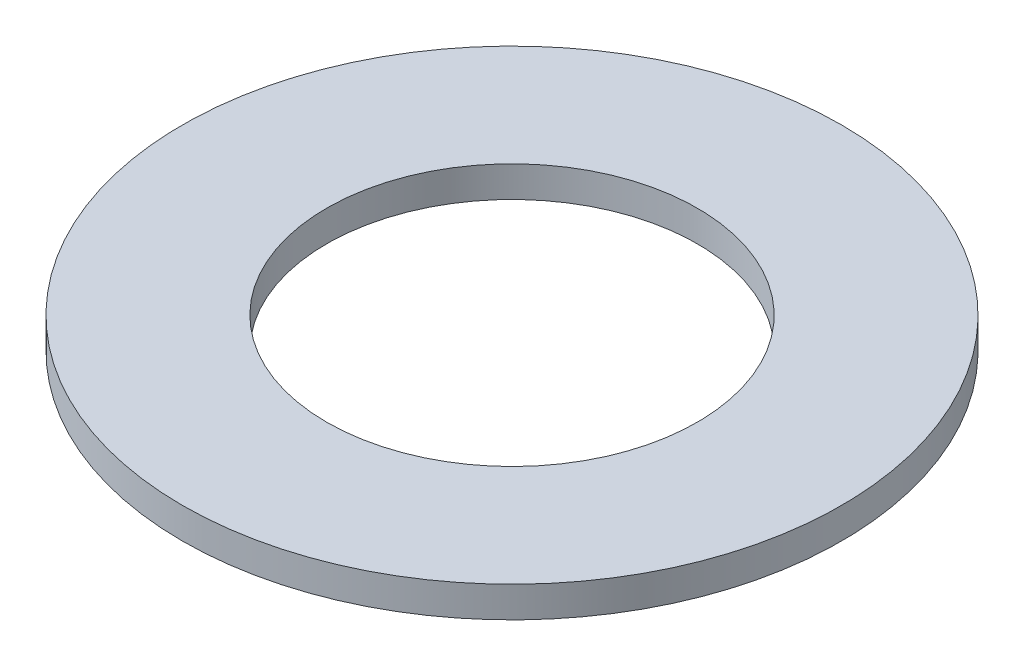
SolidWorks part; units mm, degrees
material "PA Type 6"
ref_plane "Front Plane" through (0, 0, 0) normal (0, 0, 1) x (1, 0, 0)
ref_plane "Top Plane" through (0, 0, 0) normal (0, 1, 0) x (1, 0, 0)
ref_plane "Right Plane" through (0, 0, 0) normal (1, 0, 0) x (0, 0, -1)
sketch "Sketch1" plane through (0, 0, 0) normal (0, 1, 0) x (1, 0, 0)
  circle A0 centre (0, 0) radius 9
  circle A1 centre (0, 0) radius 16
  dimension "D1" = 18
  dimension "D2" = 32
extrude "Boss-Extrude1" add sketch "Sketch1" along normal blind 1.5
